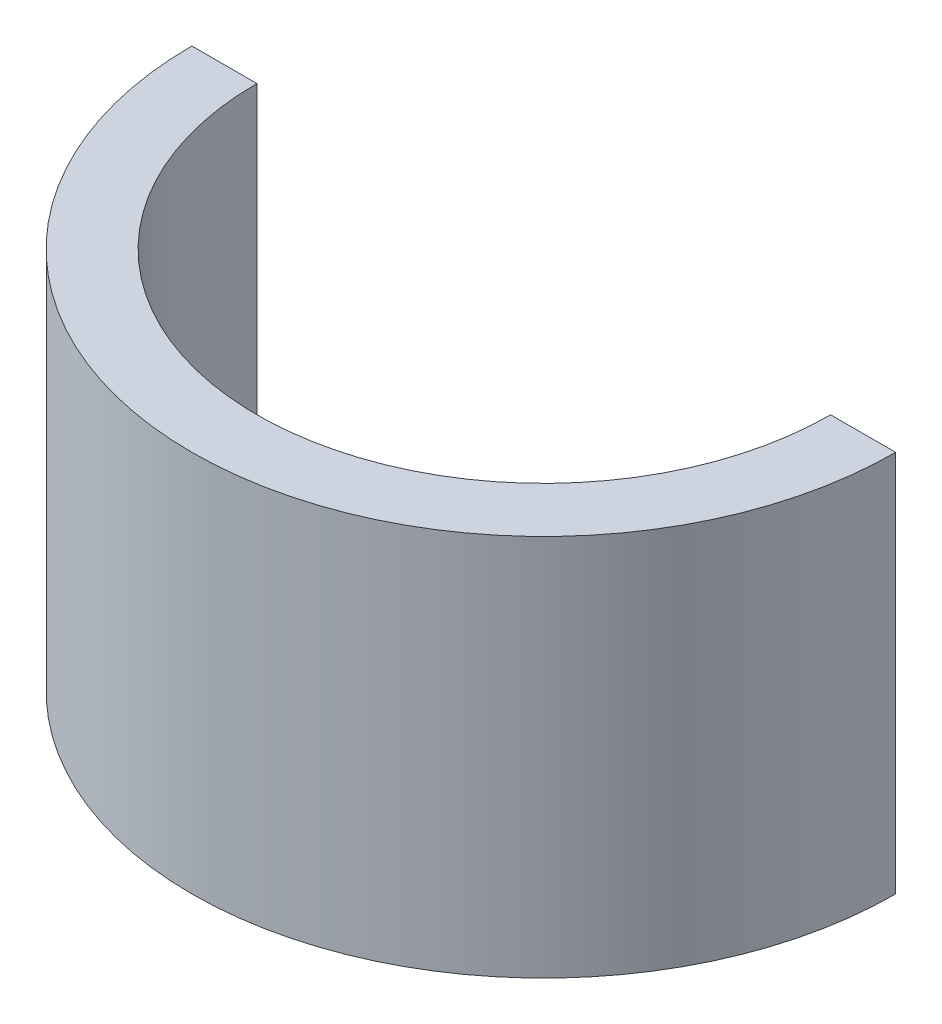
SolidWorks part; units mm, degrees
material "Phosphor bronze 10% D, UNS C52400"
ref_plane "Front Plane" through (0, 0, 0) normal (0, 0, 1) x (1, 0, 0)
ref_plane "Top Plane" through (0, 0, 0) normal (0, 1, 0) x (1, 0, 0)
ref_plane "Right Plane" through (0, 0, 0) normal (1, 0, 0) x (0, 0, -1)
sketch "Sketch1" plane through (0, 0, 0) normal (0, 1, 0) x (1, 0, 0)
  circle A0 centre (0, 0) radius 46
  circle A1 centre (0, 0) radius 37.5
  dimension "D1" = 92
  dimension "D2" = 75
extrude "Boss-Extrude1" add sketch "Sketch1" along normal blind 50
sketch "Sketch8" plane through (0, 50, 0) normal (0, 1, 0) x (1, 0, 0)
  line L1 (49.9285, 0) -> (-54.3274, 0)
  line L2 (49.9285, 0) -> (49.9285, 47.3753)
  line L3 (49.9285, 47.3753) -> (-54.3274, 47.3753)
  line L4 (-54.3274, 0) -> (-54.3274, 47.3753)
extrude "Cut-Extrude8" cut sketch "Sketch8" against normal through all both and the other way through all
